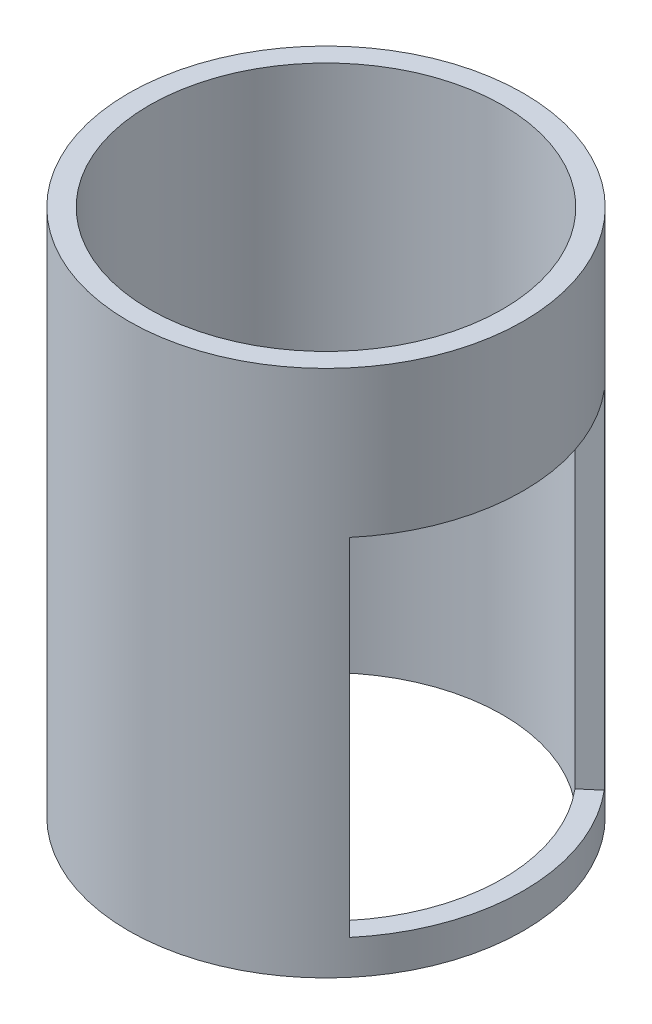
SolidWorks part; units mm, degrees
ref_plane "Front Plane" through (0, 0, 0) normal (0, 0, 1) x (1, 0, 0)
ref_plane "Top Plane" through (0, 0, 0) normal (0, 1, 0) x (1, 0, 0)
ref_plane "Right Plane" through (0, 0, 0) normal (1, 0, 0) x (0, 0, -1)
sketch "PVC" plane through (0, 0, 0) normal (0, 1, 0) x (1, 0, 0)
  circle A0 centre (0, 0) radius 57
  circle A1 centre (0, 0) radius 51
  dimension "OD" = 114
  dimension "ID" = 102
extrude "Boss-Extrude1" add sketch "PVC" along normal mid plane 152.4
sketch "Sketch1" plane through (0, -76.2, 0) normal (0, -1, 0) x (1, 0, 0)
  line L0 (0, 0) -> (43.5315, 36.7968)
  line L1 (0, 0) -> (43.5315, -36.7968)
  line L2 (0, 0) -> (-80, 0) construction
  line L3 (38.9493, 32.9235) -> (38.9493, -32.9235) construction
  line L4 (38.9493, 0) -> (51, 0) construction
  circle A0 centre (0, 0) radius 57 construction
  arc A1 (43.5315, 36.7968) -> (43.5315, -36.7968) centre (0, 0) cw
  circle A2 centre (0, 0) radius 51 construction
  point P8 (57, 0)
  dimension "D2" = 12.0507
  dimension "D1" = 80
extrude "Cut-Extrude1" cut sketch "Sketch1" against normal blind 100 from offset 10
